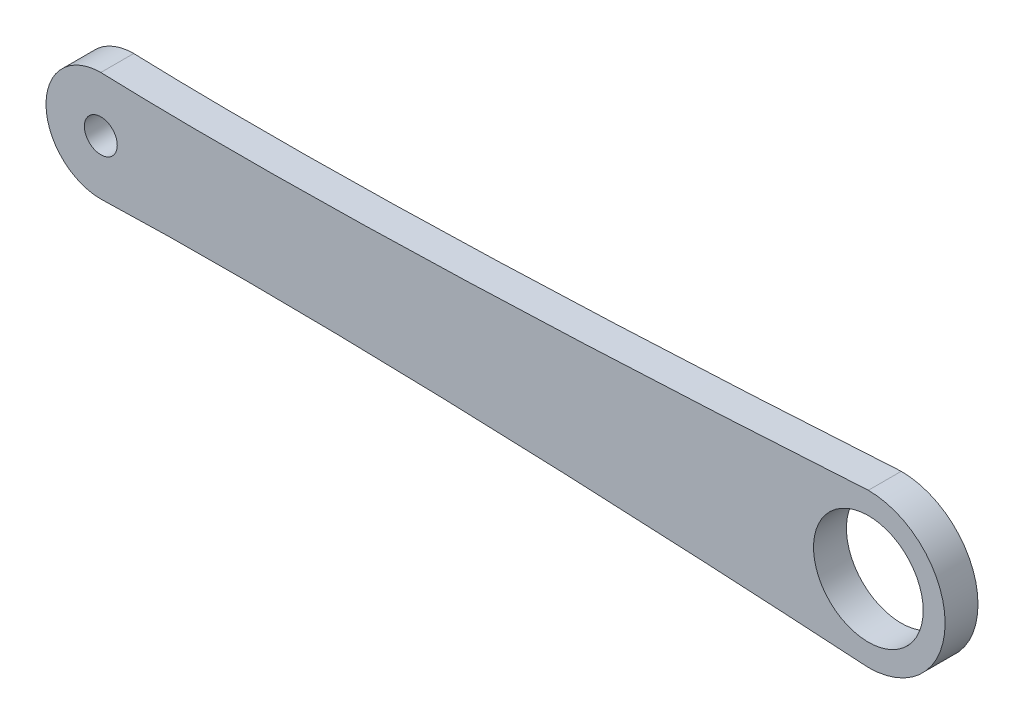
SolidWorks part; units mm, degrees
ref_plane "前视基准面" through (0, 0, 0) normal (0, 0, 1) x (1, 0, 0)
ref_plane "上视基准面" through (0, 0, 0) normal (0, 1, 0) x (1, 0, 0)
ref_plane "右视基准面" through (0, 0, 0) normal (1, 0, 0) x (0, 0, -1)
sketch "草图1" plane through (0, 0, 0) normal (0, 0, 1) x (1, 0, 0)
  line L0 (0, 0) -> (37.8488, 0) construction
  circle A0 centre (70, 0) radius 5
  circle A1 centre (0, 0) radius 1.5
  arc A2 (0, 5) -> (0, -5) centre (0, 0) ccw
  arc A4 (70, -7) -> (70, 7) centre (70, 0) ccw
  spline S0 degree 2 poles (0, 5) (24.0953, 4.1715) (70, 7) knots 0 0 0 1 1 1
  spline S1 degree 2 poles (0, -5) (24.0953, -4.1715) (70, -7) knots 0 0 0 1 1 1
  point P1 (70, 0)
  dimension "D1" = 70
extrude "凸台-拉伸2" add sketch "草图1" along normal blind 3
